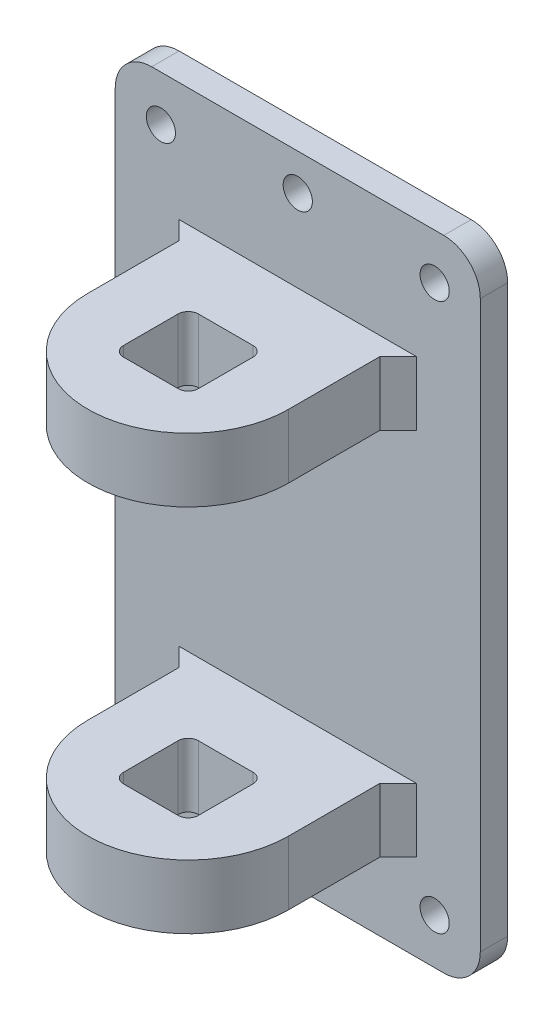
SolidWorks part; units mm, degrees
ref_plane "前视基准面" through (0, 0, 0) normal (0, 0, 1) x (1, 0, 0)
ref_plane "上视基准面" through (0, 0, 0) normal (0, 1, 0) x (1, 0, 0)
ref_plane "右视基准面" through (0, 0, 0) normal (1, 0, 0) x (0, 0, -1)
sketch "草图1" plane through (0, 0, 0) normal (0, 0, 1) x (1, 0, 0)
  line L1 (-20, -35) -> (20, -35)
  line L2 (-20, -35) -> (-20, 35)
  line L3 (-20, 35) -> (20, 35)
  line L4 (20, -35) -> (20, 35)
  line L5 (-20, -35) -> (20, 35) construction
  line L6 (-20, 35) -> (20, -35) construction
  point P0 (0, 0)
  dimension "D1" = 40
  dimension "D2" = 70
extrude "凸台-拉伸1" add sketch "草图1" along normal blind 3
sketch "草图2" plane through (0, 0, 3) normal (0, 0, 1) x (1, 0, 0)
  line L1 (-11, -30.5) -> (11, -30.5)
  line L2 (-11, -30.5) -> (-11, 30.5)
  line L3 (-11, 30.5) -> (11, 30.5)
  line L4 (11, -30.5) -> (11, 30.5)
  line L5 (-11, -30.5) -> (11, 30.5) construction
  line L6 (-11, 30.5) -> (11, -30.5) construction
  point P0 (0, 0)
  dimension "D1" = 22
  dimension "D2" = 61
extrude "凸台-拉伸2" add sketch "草图2" against normal blind 3
sketch "草图3" plane through (0, 0, 3) normal (0, 0, 1) x (1, 0, 0)
  line L1 (-11, -25.5) -> (11, -25.5)
  line L2 (-11, -25.5) -> (-11, -18.5)
  line L3 (-11, -18.5) -> (11, -18.5)
  line L4 (11, -25.5) -> (11, -18.5)
  line L5 (-11, -25.5) -> (11, -18.5) construction
  line L6 (-11, -18.5) -> (11, -25.5) construction
  point P0 (0, -22)
  dimension "D1" = 22
  dimension "D2" = 7
  dimension "D3" = 22
extrude "凸台-拉伸3" add sketch "草图3" along normal blind 12
sketch "草图4" plane through (0, -25.5, 0) normal (0, -1, 0) x (1, 0, 0)
  line L0 (-11, 15) -> (11, 15) construction
  line L1 (11, 15) -> (11, 3) construction
  circle A0 centre (0, 15) radius 11
extrude "凸台-拉伸4" add sketch "草图4" against normal up to surface (7 mm away) up to face at (0, -18.5, 9)
sketch "草图7" plane through (0, 0, 3) normal (0, 0, 1) x (1, 0, 0)
  line L1 (-15, -30) -> (15, -30) construction
  line L2 (-15, -30) -> (-15, 30) construction
  line L3 (-15, 30) -> (15, 30) construction
  line L4 (15, -30) -> (15, 30) construction
  line L5 (-15, -30) -> (15, 30) construction
  line L6 (-15, 30) -> (15, -30) construction
  circle A0 centre (-15, 30) radius 1.6
  circle A1 centre (15, 30) radius 1.6
  circle A2 centre (15, -30) radius 1.6
  circle A3 centre (-15, -30) radius 1.6
  point P0 (0, 0)
  dimension "D3" = 3.2
  dimension "D1" = 30
  dimension "D2" = 60
extrude "切除-拉伸2" cut sketch "草图7" against normal blind 7
sketch "草图8" plane through (0, 0, 3) normal (0, 0, 1) x (1, 0, 0)
  line L0 (0, -31) -> (0, 31) construction
  circle A0 centre (0, 31) radius 1.6
  circle A1 centre (0, -31) radius 1.6
  point P4 (0, 0)
  dimension "D2" = 3.2
  dimension "D1" = 62
extrude "切除-拉伸3" cut sketch "草图8" against normal blind 7
fillet "圆角1" radius 4 4 edges at (-20, 35, 1.5) (20, 35, 1.5) (20, -35, 1.5) (-20, -35, 1.5)
ref_plane "基准面1" through (0, 22, 0) normal (0, 1, 0) x (1, 0, 0)
sketch "草图9" plane through (0, 22, 0) normal (0, 1, 0) x (1, 0, 0)
  line L3 (-11, -3) -> (-11, -15)
  line L4 (11, -15) -> (11, -3)
  line L5 (11, -3) -> (-11, -3)
  line L6 (-11, -3) -> (-11, -15)
  line L7 (11, -15) -> (11, -3)
  line L8 (11, -3) -> (-11, -3)
  arc A1 (-11, -15) -> (11, -15) centre (0, -15) ccw
  arc A2 (-11, -15) -> (11, -15) centre (0, -15) ccw
  dimension "D1" = 0
extrude "凸台-拉伸5" add sketch "草图9" against normal blind 7
sketch "草图10" plane through (0, 22, 0) normal (0, 1, 0) x (1, 0, 0)
  line L1 (-3, -19) -> (3, -19)
  line L2 (-4, -18) -> (-4, -12)
  line L3 (-3, -11) -> (3, -11)
  line L4 (4, -18) -> (4, -12)
  line L5 (-4, -19) -> (4, -11) construction
  line L6 (-4, -11) -> (4, -19) construction
  arc A0 (3, -19) -> (4, -18) centre (3, -18) ccw
  arc A1 (-4, -12) -> (-3, -11) centre (-3, -12) cw
  arc A2 (-3, -19) -> (-4, -18) centre (-3, -18) cw
  arc A3 (3, -11) -> (4, -12) centre (3, -12) cw
  point P0 (0, -15)
  dimension "D3" = 1
  dimension "D1" = 8
  dimension "D2" = 8
extrude "切除-拉伸4" cut sketch "草图10" against normal through all
chamfer "倒角1" distance 2 angle 45 4 edges at (11, 18.5, 3) (-11, 18.5, 3) (-11, -22, 3) (11, -22, 3)
sketch "草图11" plane through (0, -25.5, 0) normal (0, -1, 0) x (1, 0, 0)
  line L28 (-4.1, 18) -> (-4.1, 12)
  line L29 (-3, 10.9) -> (3, 10.9)
  line L30 (4.1, 12) -> (4.1, 18)
  line L31 (3, 19.1) -> (-3, 19.1)
  line L32 (-4.1, 18) -> (-4.1, 12)
  line L33 (-3, 10.9) -> (3, 10.9)
  line L34 (4.1, 12) -> (4.1, 18)
  line L35 (3, 19.1) -> (-3, 19.1)
  arc A23 (-3, 19.1) -> (-4.1, 18) centre (-3, 18) ccw
  arc A24 (-4.1, 12) -> (-3, 10.9) centre (-3, 12) ccw
  arc A25 (3, 10.9) -> (4.1, 12) centre (3, 12) ccw
  arc A26 (4.1, 18) -> (3, 19.1) centre (3, 18) ccw
  arc A27 (-3, 19.1) -> (-4.1, 18) centre (-3, 18) ccw
  arc A28 (-4.1, 12) -> (-3, 10.9) centre (-3, 12) ccw
  arc A29 (3, 10.9) -> (4.1, 12) centre (3, 12) ccw
  arc A30 (4.1, 18) -> (3, 19.1) centre (3, 18) ccw
  dimension "D1" = 0.1
extrude "切除-拉伸5" cut sketch "草图11" against normal through all
